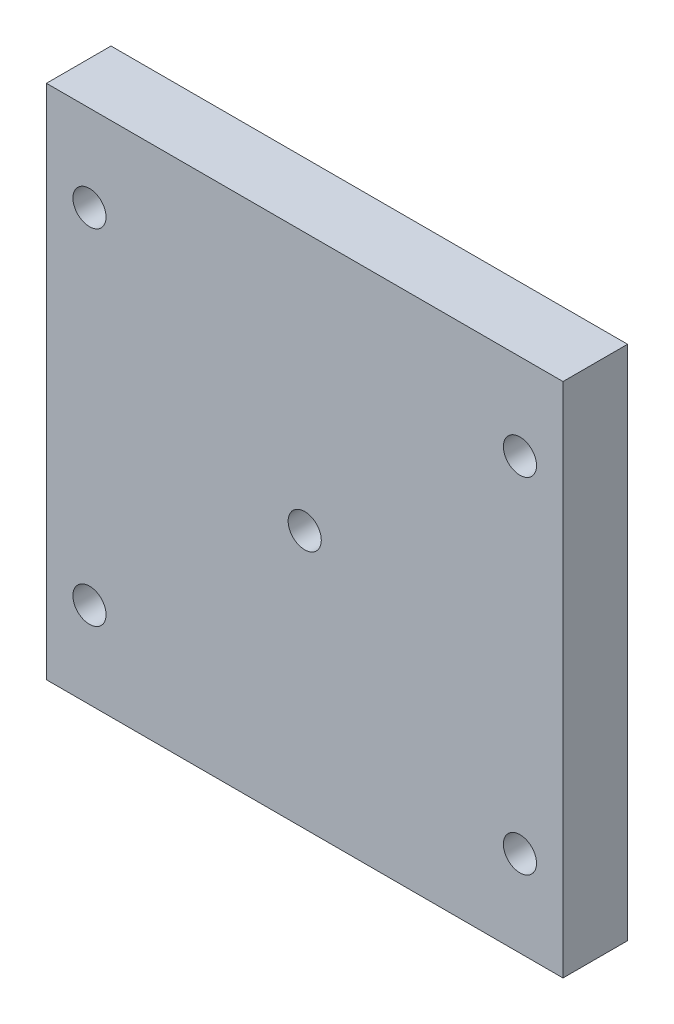
SolidWorks part; units mm, degrees
ref_plane "Front Plane" through (0, 0, 0) normal (0, 0, 1) x (1, 0, 0)
ref_plane "Top Plane" through (0, 0, 0) normal (0, 1, 0) x (1, 0, 0)
ref_plane "Right Plane" through (0, 0, 0) normal (1, 0, 0) x (0, 0, -1)
sketch "Sketch1" plane through (0, 0, 0) normal (0, 0, 1) x (1, 0, 0)
  line L1 (-152.4, 152.4) -> (152.4, 152.4)
  line L2 (-152.4, 152.4) -> (-152.4, -152.4)
  line L3 (-152.4, -152.4) -> (152.4, -152.4)
  line L4 (152.4, 152.4) -> (152.4, -152.4)
  line L5 (-152.4, 152.4) -> (152.4, -152.4) construction
  line L6 (-152.4, -152.4) -> (152.4, 152.4) construction
  point P0 (0, 0)
  dimension "D1" = 304.8
  dimension "D2" = 304.8
extrude "Boss-Extrude1" add sketch "Sketch1" along normal blind 38.1
sketch "Sketch2" plane through (0, 0, 38.1) normal (0, 0, 1) x (1, 0, 0)
  line L0 (-152.4, 0) -> (152.4, 0) construction
  line L5 (-152.4, 152.4) -> (-152.4, -152.4) construction
  line L6 (152.4, -152.4) -> (152.4, 152.4) construction
  line L7 (-152.4, -101.6) -> (152.4, -101.6) construction
  line L8 (-152.4, 101.6) -> (152.4, 101.6) construction
  line L9 (0, 101.6) -> (0, -101.6) construction
  line L10 (127, 101.6) -> (127, -101.6) construction
  line L11 (-127, 101.6) -> (-127, -101.6) construction
  circle A0 centre (-127, 101.6) radius 6.5151
  circle A1 centre (127, 101.6) radius 6.5151
  circle A2 centre (127, -101.6) radius 6.5151
  circle A3 centre (-127, -101.6) radius 6.5151
  circle A4 centre (0, 0) radius 6.5151
  dimension "D5" = 13.0302
  dimension "D1" = 101.6
  dimension "D2" = 101.6
  dimension "D3" = 127
  dimension "D4" = 127
extrude "HAAS T-Slot Holes" cut sketch "Sketch2" against normal through all
sketch "Sketch3" plane through (0, 0, 38.1) normal (0, 0, 1) x (1, 0, 0)
  circle A0 centre (-127, 101.6) radius 9.779
  circle A1 centre (127, 101.6) radius 9.779
  circle A2 centre (0, 0) radius 9.779
  circle A3 centre (127, -101.6) radius 9.779
  circle A4 centre (-127, -101.6) radius 9.779
  dimension "D1" = 19.558
extrude "HAAS Counter Bores" cut sketch "Sketch3" against normal offset from surface (22.225 mm away) 15.875 contours A0 | A1 | A2 | A3 | A4 up to face at (6.5151, 0, 0)
